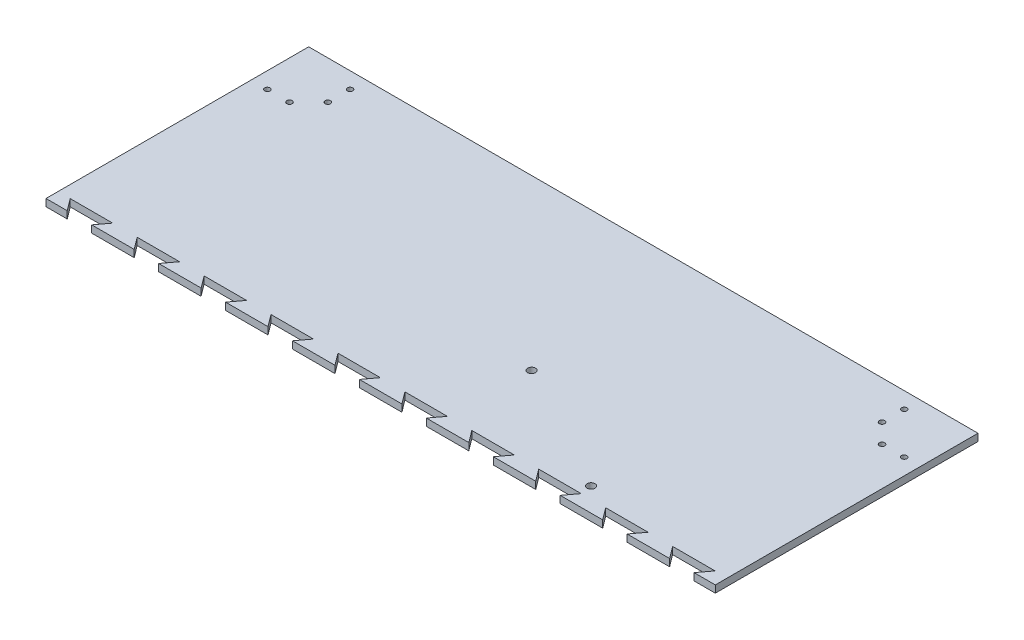
SolidWorks part; units mm, degrees
material "Multistrato di pioppo"
ref_plane "Piano frontale" through (0, 0, 0) normal (0, 0, 1) x (1, 0, 0)
ref_plane "Piano superiore" through (0, 0, 0) normal (0, 1, 0) x (1, 0, 0)
ref_plane "Piano destro" through (0, 0, 0) normal (1, 0, 0) x (0, 0, -1)
sketch "Schizzo1" plane through (0, 0, 0) normal (0, 1, 0) x (1, 0, 0)
  line L1 (-279, 219) -> (279, 219)
  line L2 (-279, 219) -> (-279, -219)
  line L3 (-279, -219) -> (279, -219)
  line L4 (279, 219) -> (279, -219)
  line L5 (-279, 219) -> (279, -219) construction
  line L6 (-279, -219) -> (279, 219) construction
  point P4 (0, 0)
  dimension "D1" = 558
  dimension "D2" = 438
extrude "Estrusione-Estrusione1" add sketch "Schizzo1" along normal blind 6
sketch "Schizzo2" plane through (0, 6, 0) normal (0, 1, 0) x (1, 0, 0)
  circle A0 centre (-231, 205.5) radius 2.25
  circle A1 centre (-231, 187) radius 2.25
  circle A2 centre (-247, 171) radius 2.25
  circle A3 centre (-265.5, 171) radius 2.25
  circle A4 centre (231, 205.5) radius 2.25
  circle A5 centre (231, 187) radius 2.25
  circle A6 centre (247, 171) radius 2.25
  circle A7 centre (265.5, 171) radius 2.25
  circle A8 centre (265.5, -171) radius 2.25
  circle A9 centre (247, -171) radius 2.25
  circle A10 centre (231, -187) radius 2.25
  circle A11 centre (231, -205.5) radius 2.25
  circle A12 centre (-231, -205.5) radius 2.25
  circle A13 centre (-231, -187) radius 2.25
  circle A14 centre (-247, -171) radius 2.25
  circle A15 centre (-265.5, -171) radius 2.25
  dimension "D1" = 4.5
extrude "Taglio-Estrusione1" cut sketch "Schizzo2" against normal blind 10
sketch "Schizzo4" plane through (0, 6, 0) normal (0, 1, 0) x (1, 0, 0)
  line L0 (279, -219) -> (279, 219) construction
  line L1 (279, 219) -> (-279, 219) construction
  line L2 (-279, -219) -> (279, -219) construction
  line L3 (-279, 219) -> (-279, -219) construction
  line L4 (-11.0471, -29.9509) -> (72.3592, -5.1397) construction
  line L5 (72.3592, -5.1397) -> (47.5479, 78.2666) construction
  line L6 (72.3592, -5.1397) -> (97.1704, -88.546) construction
  circle A0 centre (-11.0471, -29.9509) radius 3.3
  circle A1 centre (97.1704, -88.546) radius 3.3
  circle A2 centre (155.7655, 19.6716) radius 3.3
  circle A3 centre (47.5479, 78.2666) radius 3.3
  circle A4 centre (72.3592, -5.1397) radius 87.0184 construction
  dimension "D1" = 6.6
  dimension "D3" = 199.3284
  dimension "D4" = 174.0369
  dimension "D2" = 123.2345
  dimension "D5" = 189.0491
  dimension "D6" = 267.9529
  dimension "D7" = 90
extrude "Taglio-Estrusione2" cut sketch "Schizzo4" against normal blind 10
sketch "Schizzo5" plane through (0, 0, 0) normal (0, -1, 0) x (1, 0, 0)
  line L0 (-279, -219) -> (-279, 219) construction
  line L1 (-279, 219) -> (279, 219) construction
  line L2 (-136.9216, 165.1352) -> (-136.9216, 145.1352) construction
  circle A2 centre (-136.9216, 165.1352) radius 2.25
  circle A3 centre (-136.9216, 145.1352) radius 2.25
  dimension "D4" = 4.5
  dimension "D1" = 20
  dimension "D2" = 142.0784
  dimension "D3" = 73.8648
extrude "Taglio-Estrusione3" cut sketch "Schizzo5" against normal blind 10
sketch "Schizzo6" plane through (0, 6, 0) normal (0, 1, 0) x (1, 0, 0)
  line L0 (-279, 0) -> (-261.3, 0)
  line L1 (-279, 0) -> (-279, -219)
  line L2 (-279, -219) -> (279, -219)
  line L3 (-279, 219) -> (-279, -219) construction
  line L4 (-261.3, 0) -> (-268.8, 10)
  line L5 (-268.8, 10) -> (-233.4, 10)
  line L6 (-233.4, 10) -> (-240.9, 0)
  line L7 (-240.9, 0) -> (-223.2, 0)
  line L8 (-261.3, 0) -> (-240.9, 0) construction
  line L9 (-251.1, 0) -> (-251.1, 10) construction
  line L10 (279, -219) -> (279, 0)
  line L11 (-223.2, 0) -> (-205.5, 0)
  line L12 (-205.5, 0) -> (-213, 10)
  line L13 (-213, 10) -> (-177.6, 10)
  line L14 (-177.6, 10) -> (-185.1, 0)
  line L15 (-185.1, 0) -> (-167.4, 0)
  line L16 (-205.5, 0) -> (-185.1, 0) construction
  line L17 (-195.3, 0) -> (-195.3, 10) construction
  line L18 (-167.4, 0) -> (-149.7, 0)
  line L19 (-149.7, 0) -> (-157.2, 10)
  line L20 (-157.2, 10) -> (-121.8, 10)
  line L21 (-121.8, 10) -> (-129.3, 0)
  line L22 (-129.3, 0) -> (-111.6, 0)
  line L23 (-149.7, 0) -> (-129.3, 0) construction
  line L24 (-139.5, 0) -> (-139.5, 10) construction
  line L25 (-111.6, 0) -> (-93.9, 0)
  line L26 (-93.9, 0) -> (-101.4, 10)
  line L27 (-101.4, 10) -> (-66, 10)
  line L28 (-66, 10) -> (-73.5, 0)
  line L29 (-73.5, 0) -> (-55.8, 0)
  line L30 (-93.9, 0) -> (-73.5, 0) construction
  line L31 (-83.7, 0) -> (-83.7, 10) construction
  line L32 (-55.8, 0) -> (-38.1, 0)
  line L33 (-38.1, 0) -> (-45.6, 10)
  line L34 (-45.6, 10) -> (-10.2, 10)
  line L35 (-10.2, 10) -> (-17.7, 0)
  line L36 (-17.7, 0) -> (0, 0)
  line L37 (-38.1, 0) -> (-17.7, 0) construction
  line L38 (-27.9, 0) -> (-27.9, 10) construction
  line L39 (0, 0) -> (17.7, 0)
  line L40 (17.7, 0) -> (10.2, 10)
  line L41 (10.2, 10) -> (45.6, 10)
  line L42 (45.6, 10) -> (38.1, 0)
  line L43 (38.1, 0) -> (55.8, 0)
  line L44 (17.7, 0) -> (38.1, 0) construction
  line L45 (27.9, 0) -> (27.9, 10) construction
  line L46 (55.8, 0) -> (73.5, 0)
  line L47 (73.5, 0) -> (66, 10)
  line L48 (66, 10) -> (101.4, 10)
  line L49 (101.4, 10) -> (93.9, 0)
  line L50 (93.9, 0) -> (111.6, 0)
  line L51 (73.5, 0) -> (93.9, 0) construction
  line L52 (83.7, 0) -> (83.7, 10) construction
  line L53 (111.6, 0) -> (129.3, 0)
  line L54 (129.3, 0) -> (121.8, 10)
  line L55 (121.8, 10) -> (157.2, 10)
  line L56 (157.2, 10) -> (149.7, 0)
  line L57 (149.7, 0) -> (167.4, 0)
  line L58 (129.3, 0) -> (149.7, 0) construction
  line L59 (139.5, 0) -> (139.5, 10) construction
  line L60 (167.4, 0) -> (185.1, 0)
  line L61 (185.1, 0) -> (177.6, 10)
  line L62 (177.6, 10) -> (213, 10)
  line L63 (213, 10) -> (205.5, 0)
  line L64 (205.5, 0) -> (223.2, 0)
  line L65 (185.1, 0) -> (205.5, 0) construction
  line L66 (195.3, 0) -> (195.3, 10) construction
  line L67 (223.2, 0) -> (240.9, 0)
  line L68 (240.9, 0) -> (233.4, 10)
  line L69 (233.4, 10) -> (268.8, 10)
  line L70 (268.8, 10) -> (261.3, 0)
  line L71 (261.3, 0) -> (279, 0)
  line L72 (240.9, 0) -> (261.3, 0) construction
  line L73 (251.1, 0) -> (251.1, 10) construction
  line L74 (279, -219) -> (279, 219) construction
  dimension "D1" = 55.8
  dimension "D2" = 10
  dimension "D3" = 35.4
  dimension "D4" = 20.4
  dimension "D5" = 10
extrude "Taglio-Estrusione4" cut sketch "Schizzo6" against normal blind 10
